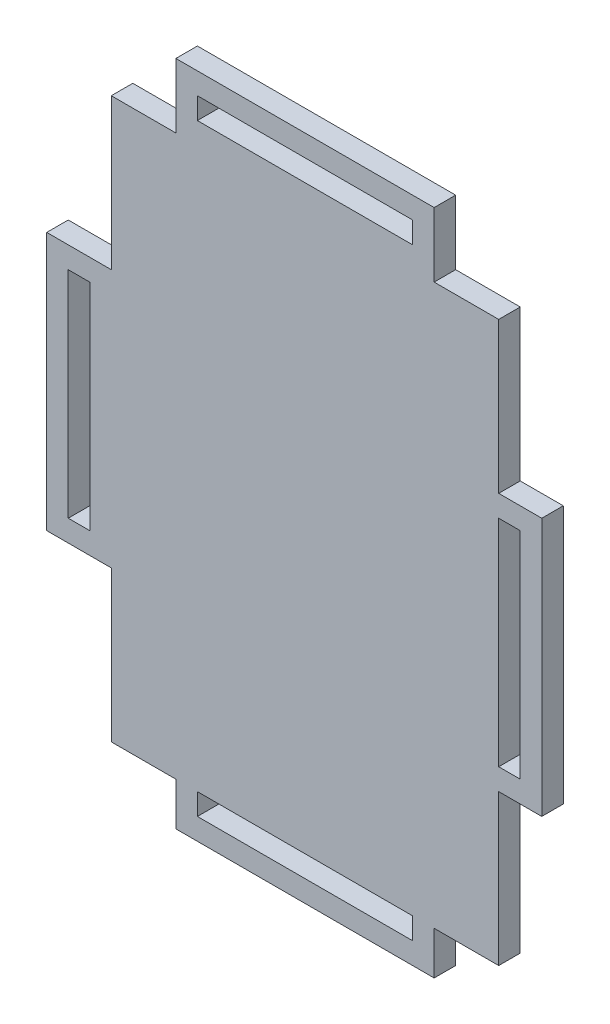
SolidWorks part; units mm, degrees
ref_plane "Front Plane" through (0, 0, 0) normal (0, 0, 1) x (1, 0, 0)
ref_plane "Top Plane" through (0, 0, 0) normal (0, 1, 0) x (1, 0, 0)
ref_plane "Right Plane" through (0, 0, 0) normal (1, 0, 0) x (0, 0, -1)
sketch "Sketch1" plane through (0, 0, 0) normal (0, 0, 1) x (1, 0, 0)
  line L1 (0, 0) -> (-90, 0)
  line L2 (0, 0) -> (0, -130)
  line L3 (0, -130) -> (-90, -130)
  line L4 (-90, 0) -> (-90, -130)
  dimension "D1" = 130
  dimension "D2" = 90
extrude "Boss-Extrude1" add sketch "Sketch1" along normal blind 5
sketch "Sketch2" plane through (0, 0, 5) normal (0, 0, 1) x (1, 0, 0)
  line L0 (0, 0) -> (-90, 0) construction
  line L1 (-70, 5) -> (-20, 5)
  line L2 (-70, 5) -> (-70, 10)
  line L3 (-70, 10) -> (-20, 10)
  line L4 (-20, 5) -> (-20, 10)
  line L5 (-90, 0) -> (-90, -130) construction
  line L12 (-75, 0) -> (-15, 0)
  line L13 (-75, 0) -> (-75, 15)
  line L14 (-75, 15) -> (-15, 15)
  line L15 (-15, 0) -> (-15, 15)
  line L16 (-15, -130) -> (-15, -140)
  line L17 (-75, -140) -> (-15, -140)
  line L18 (-75, -130) -> (-75, -140)
  line L19 (-75, -130) -> (-15, -130)
  line L20 (-20, -130) -> (-20, -135)
  line L21 (-70, -135) -> (-20, -135)
  line L22 (-70, -130) -> (-70, -135)
  line L23 (-70, -130) -> (-20, -130)
  point P8 (-70, 7.5)
  line M14 (0, 0) -> (-90, 0)
  line M16 (-90, -130) -> (0, -130)
  dimension "D1" = 5
  dimension "D2" = 50
  dimension "D3" = 20
  dimension "D4" = 5
  dimension "D5" = 5
  dimension "D6" = 5
  dimension "D7" = 15
extrude "Boss-Extrude2" add sketch "Sketch2" against normal blind 5 contours L15 L14 L13 L2 L3 L4 M14 | L22 L18 L17 L16 L19 L20 L21 M16
sketch "Sketch3" plane through (0, 0, 5) normal (0, 0, 1) x (1, 0, 0)
  line L11 (-45, 0) -> (-45, -21.5505) construction
  line L12 (-20, 0) -> (-70, 0) construction
  line L13 (10, -95) -> (10, -35)
  line L14 (0, -35) -> (10, -35)
  line L15 (0, -95) -> (0, -35)
  line L16 (0, -95) -> (10, -95)
  line L17 (5, -90) -> (5, -40)
  line L18 (0, -40) -> (5, -40)
  line L19 (0, -90) -> (0, -40)
  line L20 (0, -90) -> (5, -90)
extrude "Boss-Extrude3" add sketch "Sketch3" against normal blind 5
sketch "Sketch4" plane through (0, 0, 0) normal (0, 0, -1) x (-1, 0, 0)
  line L0 (90, 0) -> (90, -130) construction
  line L1 (90, -35) -> (105, -35)
  line L2 (90, -35) -> (90, -95)
  line L3 (90, -95) -> (105, -95)
  line L4 (105, -35) -> (105, -95)
  line L5 (75, 0) -> (90, 0) construction
  line L6 (95, -40) -> (100, -40)
  line L7 (95, -40) -> (95, -90)
  line L8 (95, -90) -> (100, -90)
  line L9 (100, -40) -> (100, -90)
  point P10 (105, -65)
  point P13 (97.5, -90)
  dimension "D1" = 15
  dimension "D2" = 5
  dimension "D3" = 5
  dimension "D4" = 60
  dimension "D5" = 65
  dimension "D6" = 50
  dimension "D7" = 5
extrude "Boss-Extrude4" add sketch "Sketch4" against normal blind 5
